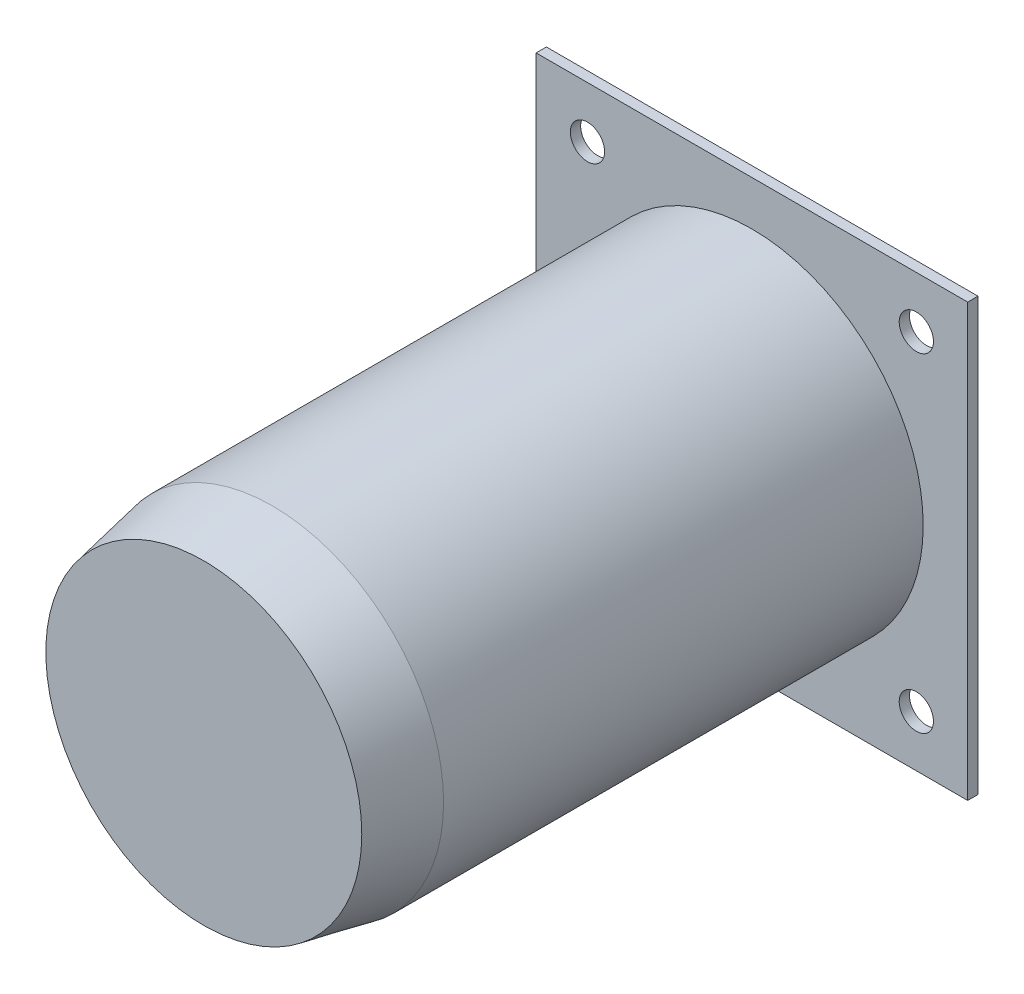
SolidWorks part; units mm, degrees
ref_plane "Front Plane" through (0, 0, 0) normal (0, 0, 1) x (1, 0, 0)
ref_plane "Top Plane" through (0, 0, 0) normal (0, 1, 0) x (1, 0, 0)
ref_plane "Right Plane" through (0, 0, 0) normal (1, 0, 0) x (0, 0, -1)
sketch "Sketch1" plane through (0, 0, 0) normal (0, 0, 1) x (1, 0, 0)
  line L1 (-31.5, -31.5) -> (31.5, -31.5)
  line L2 (-31.5, -31.5) -> (-31.5, 31.5)
  line L3 (-31.5, 31.5) -> (31.5, 31.5)
  line L4 (31.5, -31.5) -> (31.5, 31.5)
  line L5 (-31.5, -31.5) -> (31.5, 31.5) construction
  line L6 (-31.5, 31.5) -> (31.5, -31.5) construction
  circle A0 centre (24, 24) radius 2.5
  circle A1 centre (24, -24) radius 2.5
  circle A2 centre (-24, -24) radius 2.5
  circle A3 centre (-24, 24) radius 2.5
  point P0 (0, 0)
  point P17 (0, 0)
  dimension "D2" = 5
  dimension "D1" = 63
  dimension "D3" = 7.5
  dimension "D4" = 7.5
  dimension "D5" = 4
extrude "Boss-Extrude1" add sketch "Sketch1" along normal blind 1.5
sketch "Sketch2" plane through (0, 0, 1.5) normal (0, 0, 1) x (1, 0, 0)
  circle A0 centre (0, 0) radius 25
  dimension "D1" = 50
extrude "Boss-Extrude2" add sketch "Sketch2" along normal blind 80
chamfer "Chamfer1" distance 10 angle 11 1 edges at (25, 0, 81.5)
